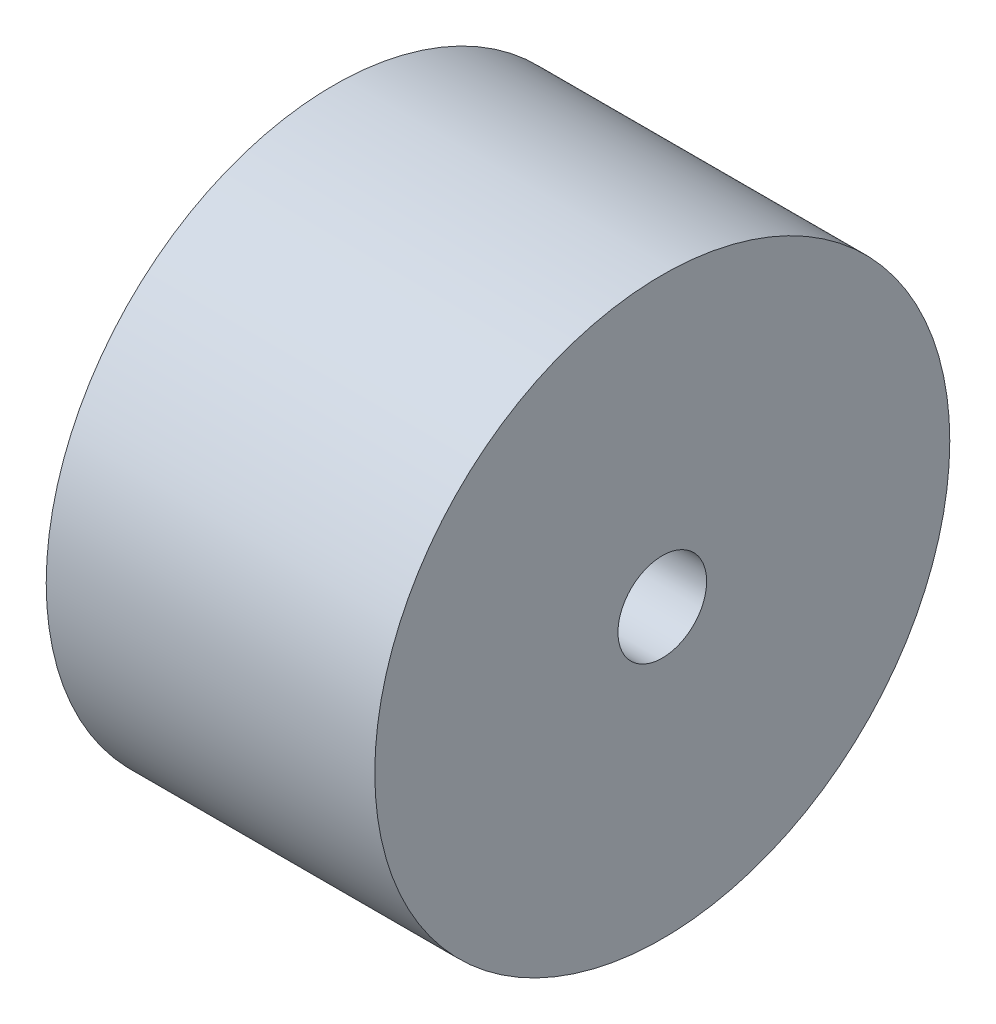
SolidWorks part; units mm, degrees
ref_plane "Alzado" through (0, 0, 0) normal (0, 0, 1) x (1, 0, 0)
ref_plane "Planta" through (0, 0, 0) normal (0, 1, 0) x (1, 0, 0)
ref_plane "Vista lateral" through (0, 0, 0) normal (1, 0, 0) x (0, 0, -1)
sketch "Croquis1" plane through (0, 0, 0) normal (1, 0, 0) x (0, 0, -1)
  circle A0 centre (0, 0) radius 17.5
  dimension "D1" = 35
extrude "Saliente-Extruir1" add sketch "Croquis1" along normal blind 20
sketch "Croquis2" plane through (20, 0, 0) normal (1, 0, 0) x (0, 0, -1)
  circle A0 centre (0, 0) radius 2.7
  dimension "D1" = 5.4
extrude "Cortar-Extruir1" cut sketch "Croquis2" against normal through all
